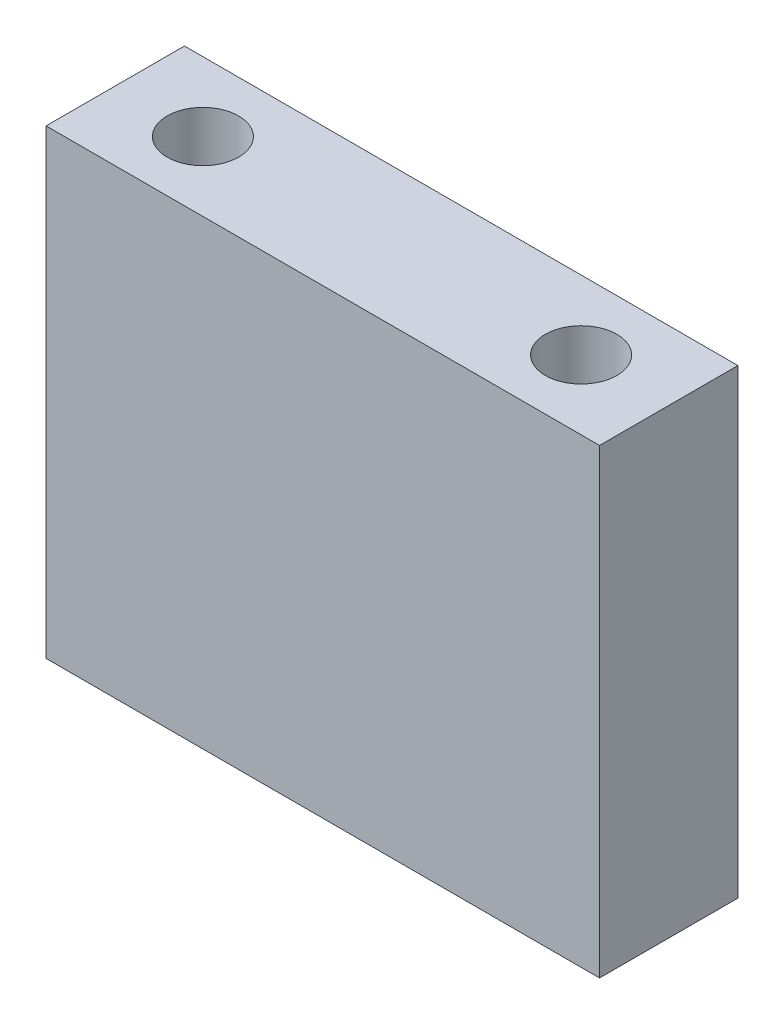
SolidWorks part; units mm, degrees
ref_plane "정면" through (0, 0, 0) normal (0, 0, 1) x (1, 0, 0)
ref_plane "윗면" through (0, 0, 0) normal (0, 1, 0) x (1, 0, 0)
ref_plane "우측면" through (0, 0, 0) normal (1, 0, 0) x (0, 0, -1)
sketch "스케치1" plane through (0, 0, 0) normal (0, 1, 0) x (1, 0, 0)
  line L1 (0, 0) -> (120, 0)
  line L2 (0, 0) -> (0, 30)
  line L3 (0, 30) -> (120, 30)
  line L4 (120, 0) -> (120, 30)
  dimension "D1" = 120
  dimension "D2" = 30
extrude "보스-돌출1" add sketch "스케치1" along normal blind 100
sketch "스케치2" plane through (0, 100, 0) normal (0, 1, 0) x (1, 0, 0)
  line L0 (120, 0) -> (120, 30) construction
  line L1 (120, 30) -> (0, 30) construction
  circle A0 centre (101, 15) radius 7.75
  circle A1 centre (19, 15) radius 7.75
  point P4 (0, 0)
  point P7 (120, 15)
  point P10 (60, 30)
  dimension "D3" = 15.5
  dimension "D1" = 82
  dimension "D2" = 41
extrude "컷-돌출1" cut sketch "스케치2" against normal blind 1000
